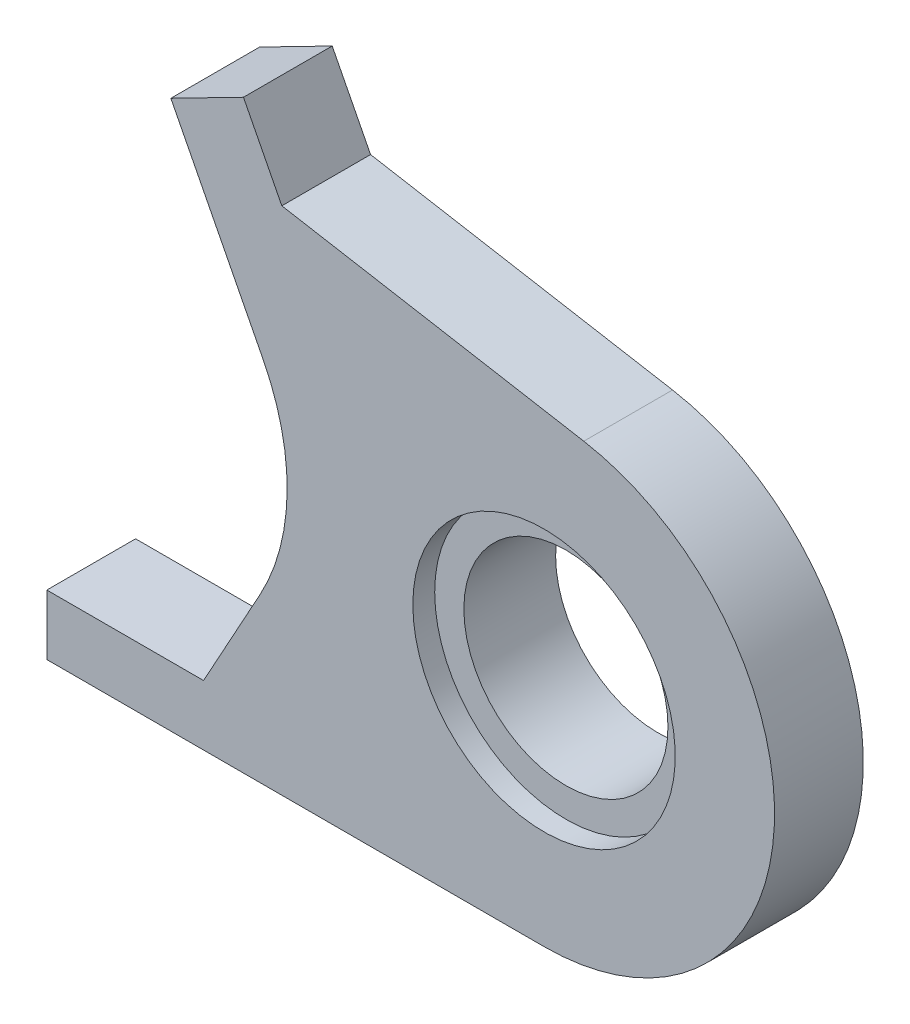
SolidWorks part; units mm, degrees
ref_plane "Front Plane" through (0, 0, 0) normal (0, 0, 1) x (1, 0, 0)
ref_plane "Top Plane" through (0, 0, 0) normal (0, 1, 0) x (1, 0, 0)
ref_plane "Right Plane" through (0, 0, 0) normal (1, 0, 0) x (0, 0, -1)
sketch "Sketch1" plane through (0, 0, 0) normal (0, 1, 0) x (1, 0, 0)
  line L0 (-90, -29.7958) -> (-90, -14.7958)
  line L1 (-90, -14.7958) -> (-70, -14.7958)
  line L2 (-70, -14.7958) -> (-70, 48.1404)
  line L3 (-70, 48.1404) -> (-99.097, 48.1404)
  line L4 (-99.097, 48.1404) -> (-99.097, 31.0695)
  line L5 (-99.097, 31.0695) -> (-158.1136, 31.0695)
  line L6 (-158.1136, 31.0695) -> (-158.1136, -29.7958)
  line L7 (-158.1136, -29.7958) -> (-90, -29.7958)
  line L8 (0, 0) -> (0, -201.5279) construction
revolve "Revolve1" add sketch "Sketch1" angle 360 about L8
sketch "Sketch2" plane through (0, 0, -31.0695) normal (0, 0, -1) x (-1, 0, 0)
  line L8 (0, -158.1136) -> (341.0276, -158.1136)
  line L9 (341.0276, -158.1136) -> (341.0276, -116.8069)
  line L10 (341.0276, -116.8069) -> (233.5351, -116.8069)
  line L11 (233.5351, -116.8069) -> (194.7608, -46.3207)
  line L12 (192.6983, 94.3917) -> (255.9599, 217.8267)
  line L13 (255.9599, 217.8267) -> (206.1596, 243.3498)
  line L14 (206.1596, 243.3498) -> (179.8473, 192.0097)
  line L15 (179.8473, 192.0097) -> (-27.2702, 155.7441)
  arc A4 (-27.2702, 155.7441) -> (0, -158.1136) centre (0, 0) ccw
  circle A5 centre (0, 0) radius 158.1136 construction
  arc A6 (194.7608, -46.3207) -> (192.6983, 94.3917) centre (326.1877, 25.977) cw
  circle A7 centre (0, 0) radius 90
  circle A8 centre (0, 0) radius 90 construction
  dimension "D1" = 150
extrude "Boss-Extrude1" add sketch "Sketch2" against normal up to surface (60.8653 mm away) up to face at (-90, 0, 29.7958)
